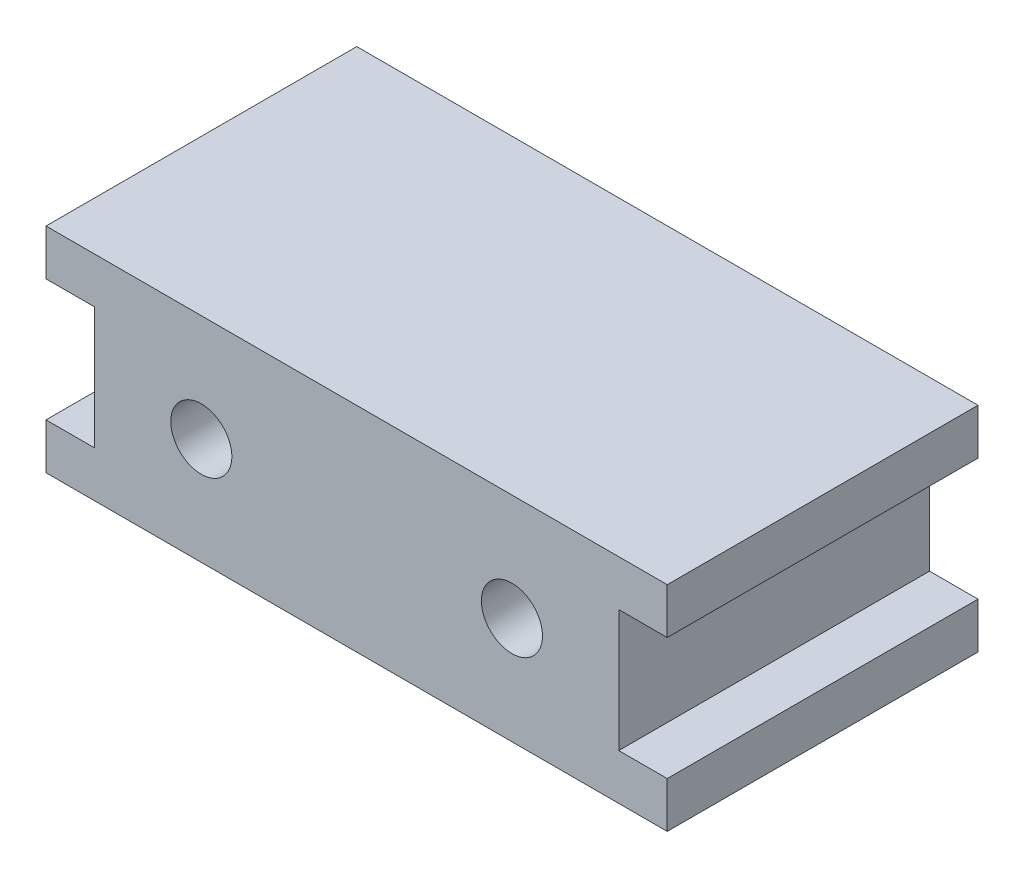
SolidWorks part; units mm, degrees
ref_plane "Front Plane" through (0, 0, 0) normal (0, 0, 1) x (1, 0, 0)
ref_plane "Top Plane" through (0, 0, 0) normal (0, 1, 0) x (1, 0, 0)
ref_plane "Right Plane" through (0, 0, 0) normal (1, 0, 0) x (0, 0, -1)
sketch "Sketch1" plane through (0, 0, 0) normal (0, 0, 1) x (1, 0, 0)
  line L0 (0, 34.6926) -> (0, -34.8428) construction
  line L1 (40.7, -3.6775) -> (40.7, -9.6775)
  line L2 (-40.7, 18.3225) -> (40.7, 18.3225)
  line L3 (0, 18.3225) -> (0, -9.6775)
  line L4 (-40.7, -9.6775) -> (40.7, -9.6775)
  line L5 (40.7, 18.3225) -> (40.7, 12.3225)
  line L6 (40.7, 12.3225) -> (34.35, 12.3225)
  line L8 (40.7, -3.6775) -> (34.35, -3.6775)
  line L9 (34.35, 12.3225) -> (34.35, -3.6775)
  line L10 (-34.35, 12.3225) -> (-34.35, -3.6775)
  line L11 (-40.7, -3.6775) -> (-34.35, -3.6775)
  line L12 (-40.7, 12.3225) -> (-34.35, 12.3225)
  line L13 (-40.7, 18.3225) -> (-40.7, 12.3225)
  line L14 (-40.7, -3.6775) -> (-40.7, -9.6775)
  circle A0 centre (20.35, 4.3225) radius 4
  circle A1 centre (-20.35, 4.3225) radius 4
  dimension "D9" = 8
  dimension "D1" = 40.7
  dimension "D2" = 28
  dimension "D3" = 6.35
  dimension "D4" = 6
  dimension "D5" = 6
  dimension "D6" = 16
  dimension "D7" = 20.35
  dimension "D8" = 14
extrude "Boss-Extrude1" add sketch "Sketch1" against normal blind 40.72 contours L4 L1 L8 L9 L6 L5 L2 L13 L12 L10 L11 L14 | A1 | A0
